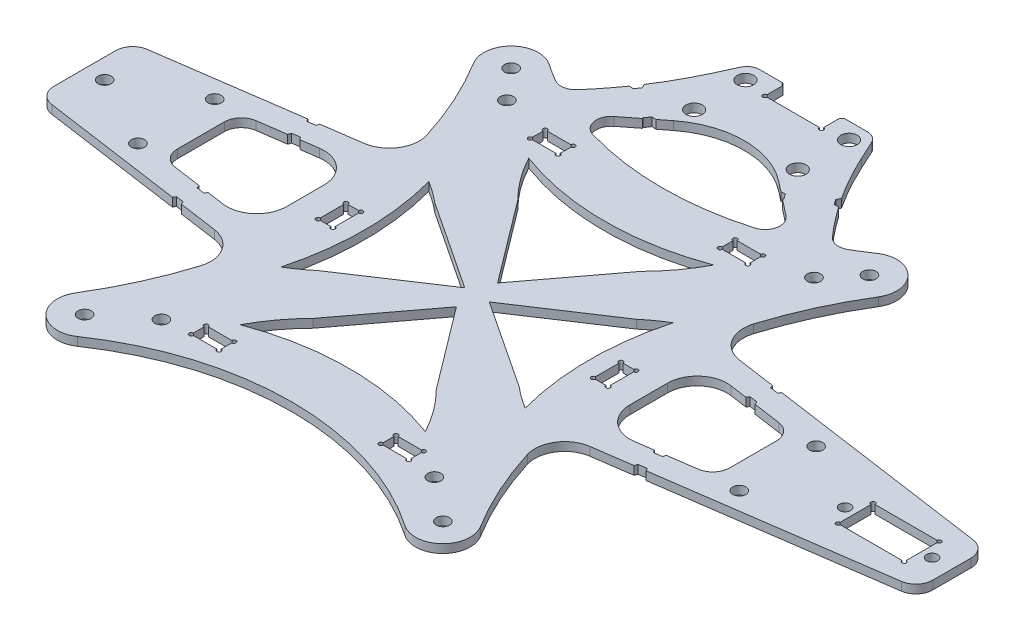
SolidWorks part; units mm, degrees
other "细节项目1" parameters "D5"=3.1, "D18"=3.2, "D24"=1.84, "D6"=8.6708, "D11"=4.977, "D15"=5.1762, "D16"=1.6515, "D17"=3.1, "D21"=13.484, "D14"=3.1, "D32"=6.4038, "D1"=40.7355, "D2"=35.8432, "D3"=28, "D4"=40.1699, "D7"=36.5, "D8"=41.25, "D9"=46.5, "D10"=20, "D12"=32.5, "D13"=87.0157, "D19"=3.5, "D20"=2.5, "D22"=0.15, "D23"=0.525, "D25"=70.5, "D26"=9, "D27"=9, "D28"=9.5, "D29"=135, "D30"=15.9142, "D31"=16.8571, "D33"=75.3972
material "PPS"
ref_plane "前视基准面" through (0, 0, 0) normal (0, 0, 1) x (1, 0, 0)
ref_plane "上视基准面" through (0, 0, 0) normal (0, 1, 0) x (1, 0, 0)
ref_plane "右视基准面" through (0, 0, 0) normal (1, 0, 0) x (0, 0, -1)
sketch "草图1" plane through (0, 0, 0) normal (0, 1, 0) x (1, 0, 0)
  line L3 (-133.7177, 0) -> (146.3754, 0) construction
  line L56 (0, 96.0639) -> (0, -115.1457) construction
  line L65 (-25.5, 41.5) -> (-19, 41.5)
  line L66 (-34, 3.25) -> (-30.5, 3.25)
  line L70 (-34, 3.25) -> (-34, -3.25)
  line L76 (-34, -3.25) -> (-30.5, -3.25)
  line L80 (-30.5, 3.25) -> (-30.5, -3.25)
  line L81 (-25.5, -38) -> (-19, -38)
  line L82 (-25.5, -38) -> (-25.5, -41.5)
  line L83 (-25.5, -41.5) -> (-19, -41.5)
  line L84 (-19, -38) -> (-19, -41.5)
  line L85 (-19, 38) -> (-19, 41.5)
  line L86 (-25.5, 38) -> (-19, 38)
  line L142 (-25.5, 38) -> (-25.5, 41.5)
  line L143 (25.5, 38) -> (25.5, 41.5)
  line L144 (25.5, 38) -> (19, 38)
  line L145 (19, 38) -> (19, 41.5)
  line L146 (19, -38) -> (19, -41.5)
  line L147 (25.5, -41.5) -> (19, -41.5)
  line L148 (25.5, -38) -> (25.5, -41.5)
  line L149 (25.5, -38) -> (19, -38)
  line L150 (30.5, 3.25) -> (30.5, -3.25)
  line L151 (34, -3.25) -> (30.5, -3.25)
  line L152 (34, 3.25) -> (34, -3.25)
  line L153 (34, 3.25) -> (30.5, 3.25)
  line L154 (25.5, 41.5) -> (19, 41.5)
  line L155 (77.65, -2.1518) -> (77.65, -4) construction
  line L156 (74.85, 4) -> (77.65, 4) construction
  line L157 (74.85, 4) -> (74.85, 2.1768) construction
  line L158 (74.85, -4) -> (77.65, -4) construction
  line L159 (77.65, 4) -> (77.65, 2.1518) construction
  line L160 (74.85, -2.1768) -> (74.85, -4) construction
  line L161 (96.5, 7.6653) -> (96.5, -9.1503) construction
  line L162 (88.75, 4.1) -> (104.25, 4.1)
  line L163 (88.75, 4.1) -> (88.75, -4.1)
  line L164 (88.75, -4.1) -> (104.25, -4.1)
  line L165 (104.25, 4.1) -> (104.25, -4.1)
  line L166 (-96.5, 7.6653) -> (-96.5, -9.1503) construction
  line L171 (-74.85, -2.1768) -> (-74.85, -4) construction
  line L172 (-77.65, 4) -> (-77.65, 2.1518) construction
  line L173 (-74.85, -4) -> (-77.65, -4) construction
  line L174 (-74.85, 4) -> (-74.85, 2.1768) construction
  line L175 (-74.85, 4) -> (-77.65, 4) construction
  line L176 (-77.65, -2.1518) -> (-77.65, -4) construction
  line L177 (111.35, 7.9303) -> (111.35, -7.9303)
  line L178 (111.35, 7.9303) -> (36.25, 18.6361)
  line L179 (111.35, -7.9303) -> (36.25, -18.6361)
  line L184 (14.4296, 23.978) -> (0, 4.8247)
  line L186 (-14.4296, 23.978) -> (0, 4.8247)
  line L187 (23.6257, -13.733) -> (2.8757, 0)
  line L188 (23.6257, 13.733) -> (2.8757, 0)
  line L191 (-91.953, 10.6955) -> (-91.953, -10.6955)
  line L192 (-36.25, 18.6361) -> (-91.953, 10.6955)
  line L193 (-91.953, -10.6955) -> (-36.25, -18.6361)
  line L195 (-64.75, -8.9672) -> (-64.75, 8.9672)
  line L196 (-64.75, 8.9672) -> (-40.25, 12.4598)
  line L197 (-40.25, 12.4598) -> (-40.25, -12.4598)
  line L198 (-64.75, -8.9672) -> (-40.25, -12.4598)
  line L199 (64.75, 8.9672) -> (40.25, 12.4598)
  line L200 (40.25, 12.4598) -> (40.25, -12.4598)
  line L201 (64.75, -8.9672) -> (40.25, -12.4598)
  line L202 (64.75, 8.9672) -> (64.75, -8.9672)
  line L211 (-23.6257, 13.733) -> (-2.8757, 0)
  line L212 (-23.6257, -13.733) -> (-2.8757, 0)
  line L213 (-14.4296, -23.978) -> (0, -4.8247)
  line L214 (14.4296, -23.978) -> (0, -4.8247)
  circle A0 centre (-36, 43) radius 1.55
  circle A1 centre (-32, -42) radius 1.55
  circle A2 centre (32, -42) radius 1.55
  circle A3 centre (36, 43) radius 1.55
  circle A4 centre (42, 50) radius 1.55
  circle A5 centre (42, -50) radius 1.55
  circle A6 centre (-42, -50) radius 1.55
  circle A7 centre (-42, 50) radius 1.55
  arc A8 (74.85, 2.1768) -> (74.85, -2.1768) centre (76.2307, 0) ccw construction
  arc A9 (77.65, -2.1518) -> (77.65, 2.1518) centre (76.2307, 0) ccw construction
  circle A10 centre (106.7, 0) radius 1.3
  circle A11 centre (86.3, 0) radius 1.3
  arc A14 (-77.65, -2.1518) -> (-77.65, 2.1518) centre (-76.2307, 0) cw construction
  arc A15 (-74.85, 2.1768) -> (-74.85, -2.1768) centre (-76.2307, 0) cw construction
  arc A18 (-38.3898, 55.2892) -> (38.3898, 55.2892) centre (0, 111.5317) ccw
  arc A20 (47.4575, 46.6496) -> (36.25, 18.6361) centre (123.4458, 0) ccw
  arc A21 (47.4575, 46.6496) -> (38.3898, 55.2892) centre (42, 50) ccw
  arc A22 (-38.3898, -55.2892) -> (38.3898, -55.2892) centre (0, -111.5317) cw
  arc A23 (47.4575, -46.6496) -> (36.25, -18.6361) centre (123.4458, 0) cw
  arc A24 (47.4575, -46.6496) -> (38.3898, -55.2892) centre (42, -50) cw
  arc A26 (-47.4575, -46.6496) -> (-38.3898, -55.2892) centre (-42, -50) ccw
  arc A27 (-47.4575, -46.6496) -> (-36.25, -18.6361) centre (-123.4458, 0) ccw
  arc A28 (-47.4575, 46.6496) -> (-38.3898, 55.2892) centre (-42, 50) cw
  arc A30 (-47.4575, 46.6496) -> (-36.25, 18.6361) centre (-123.4458, 0) cw
  arc A34 (-14.4296, 23.978) -> (-21.6836, 33.816) centre (14.4807, 52.8883) cw
  arc A35 (-21.6836, 33.816) -> (21.6836, 33.816) centre (0, 91.9966) ccw
  arc A36 (14.4296, 23.978) -> (21.6836, 33.816) centre (-14.4807, 52.8883) ccw
  arc A37 (23.6257, 13.733) -> (28.6529, 17.3535) centre (49.9637, -17.5386) cw
  arc A38 (28.6529, 17.3535) -> (28.6529, -17.3535) centre (92.8745, 0) ccw
  arc A39 (23.6257, -13.733) -> (28.6529, -17.3535) centre (49.436, 16.806) ccw
  circle A43 centre (70.5, 9) radius 1.55
  circle A44 centre (70.5, -9) radius 1.55
  circle A45 centre (-70.5, -9) radius 1.55
  circle A46 centre (-70.5, 9) radius 1.55
  circle A47 centre (-87.3, 0) radius 1.55
  arc A48 (-23.6257, -13.733) -> (-28.6529, -17.3535) centre (-49.436, 16.806) cw
  arc A49 (-28.6529, 17.3535) -> (-28.6529, -17.3535) centre (-92.8745, 0) cw
  arc A50 (-23.6257, 13.733) -> (-28.6529, 17.3535) centre (-49.9637, -17.5386) ccw
  arc A51 (14.4296, -23.978) -> (21.6836, -33.816) centre (-14.4807, -52.8883) cw
  arc A52 (-21.6836, -33.816) -> (21.6836, -33.816) centre (0, -91.9966) cw
  arc A53 (-14.4296, -23.978) -> (-21.6836, -33.816) centre (14.4807, -52.8883) ccw
  point P71 (0, 0)
  point P81 (-34, 0)
  point P118 (0, 0)
  point P140 (-40.25, 0)
  point P148 (0, 0)
  point P149 (-64.75, 0)
  point P150 (0, 0)
  point P151 (34, 18.9559)
  point P152 (37.6986, 18.4296)
extrude "凸台-拉伸1" add sketch "草图1" along normal blind 2
fillet "圆角1" radius 4 8 edges at (111.35, 1, -7.9303) (111.35, 1, 7.9303) (-91.953, 1, 10.6955) (-91.953, 1, -10.6955) (-64.75, 1, 8.9672) (-64.75, 1, -8.9672) (64.75, 1, 8.9672) (64.75, 1, -8.9672)
fillet "圆角2" radius 7 8 edges at (36.25, 1, -18.6361) (36.25, 1, 18.6361) (-36.25, 1, 18.6361) (-36.25, 1, -18.6361) (40.25, 1, 12.4598) (40.25, 1, -12.4598) (-40.25, 1, 12.4598) (-40.25, 1, -12.4598)
sketch "光流接口-修改" plane through (0, 0, 0) normal (0, 1, 0) x (1, 0, 0)
  line L0 (30.4025, 52.8577) -> (32.0373, 51.0287)
  line L1 (-32.0373, 51.0287) -> (-30.4025, 52.8577)
  line L2 (-6.65, 78.8853) -> (-6.65, 74.1353)
  line L3 (-6.65, 74.1353) -> (-0.15, 74.1353)
  line L4 (-0.15, 74.1353) -> (-0.15, 78.8853) construction
  line L5 (-12.6234, 78.8853) -> (-6.65, 78.8853)
  line L6 (-0.15, 74.1353) -> (0.15, 74.1353)
  line L7 (6.65, 74.1353) -> (0.15, 74.1353)
  line L8 (0.15, 74.1353) -> (0.15, 78.8853) construction
  line L9 (6.65, 78.8853) -> (6.65, 74.1353)
  line L10 (12.6234, 78.8853) -> (6.65, 78.8853)
  line L12 (12.3359, 58.409) -> (29.4648, 44.9866)
  line L13 (15.3497, 77.1372) -> (17.348, 72.7857)
  line L14 (0, -39.4607) -> (0, 39.4607) construction
  line L15 (-15.3497, 77.1372) -> (-17.348, 72.7857)
  line L16 (-12.3359, 58.409) -> (-29.4648, 44.9866)
  line L17 (-12.6234, 78.8853) -> (12.6234, 78.8853) construction
  circle A38 centre (-12.15, 75.08) radius 1.925
  circle A39 centre (-12.15, 63.05) radius 1.925
  circle A40 centre (12.15, 63.05) radius 1.925
  circle A41 centre (12.15, 75.08) radius 1.925
  circle A42 centre (-36, 43) radius 1.55
  circle A43 centre (36, 43) radius 1.55
  arc A44 (-37.8248, 46.5595) -> (-32.3705, 41.3187) centre (-36, 43) ccw
  arc A45 (37.8248, 46.5595) -> (32.3705, 41.3187) centre (36, 43) cw
  arc A46 (32.3705, 41.3187) -> (29.4648, 44.9866) centre (23.2968, 37.1154) ccw
  arc A47 (37.8248, 46.5595) -> (32.0373, 51.0287) centre (46.9489, 64.357) cw
  arc A48 (-12.3359, 58.409) -> (12.3359, 58.409) centre (0, 42.6665) cw
  arc A49 (17.348, 72.7857) -> (30.4025, 52.8577) centre (90.0489, 106.1709) ccw
  arc A50 (12.6234, 78.8853) -> (15.3497, 77.1372) centre (12.6234, 75.8853) cw
  arc A51 (-12.6234, 78.8853) -> (-15.3497, 77.1372) centre (-12.6234, 75.8853) ccw
  arc A52 (-17.348, 72.7857) -> (-30.4025, 52.8577) centre (-90.0489, 106.1709) cw
  arc A53 (-37.8248, 46.5595) -> (-32.0373, 51.0287) centre (-46.9489, 64.357) ccw
  arc A54 (-32.3705, 41.3187) -> (-29.4648, 44.9866) centre (-23.2968, 37.1154) cw
  arc A55 (-37.8248, 46.5595) -> (-32.3705, 41.3187) centre (-36, 43) ccw
  circle A56 centre (-36, 43) radius 1.55
  point P10 (0, 78.8853)
  dimension "D4" = 3.85
  dimension "D1" = 12.03
  dimension "D2" = 24.3
  dimension "D3" = 63.05
  dimension "D5" = 5.5
  dimension "D6" = 6.5
  dimension "D7" = 4.75
extrude "凸台-拉伸2" add sketch "光流接口-修改" along normal up to surface (2 mm away) from surface at 0 contours A48 L14 L17 A51 L15 A52 L1 A53 A44 A54 L16 A42 A39 A38 | L14 A48 L12 A46 A45 A47 L0 A49 L13 A50 L17 A40 A41 A43
sketch "线槽-草图" plane through (0, 0, 0) normal (0, 1, 0) x (1, 0, 0)
  line L1 (107.9145, 8.4201) -> (44.0177, 17.5288) construction
  line L5 (57.8515, 15.5567) -> (57.0683, 10.0623) construction
  line L6 (53.6304, 11.2089) -> (53.5387, 10.5654) construction
  line L7 (57.4599, 12.8095) -> (49.4026, 13.9581) construction
  line L8 (54.5679, 11.0753) -> (52.693, 11.3426)
  line L9 (54.7762, 10.389) -> (54.5679, 11.0753)
  line L10 (52.3012, 10.7418) -> (54.7762, 10.389)
  line L11 (52.693, 11.3426) -> (52.3012, 10.7418)
  line L12 (0, 0) -> (132.6638, 0) construction
  line L21 (0, -0.7474) -> (0, 57.4396) construction
  line L38 (61.3145, 9.457) -> (48.2379, 11.3211) construction
  line L39 (54.2302, 15.4164) -> (54.322, 16.0599) construction
  line L40 (53.2928, 15.55) -> (53.0845, 16.2363)
  line L41 (53.0845, 16.2363) -> (55.5595, 15.8835)
  line L42 (55.5595, 15.8835) -> (55.1677, 15.2828)
  line L43 (55.1677, 15.2828) -> (53.2928, 15.55)
  line L44 (-54.2302, 15.4164) -> (-54.322, 16.0599) construction
  line L45 (-57.4599, 12.8095) -> (-49.4026, 13.9581) construction
  line L46 (-53.6304, 11.2089) -> (-53.5387, 10.5654) construction
  line L47 (-57.8515, 15.5567) -> (-57.0683, 10.0623) construction
  line L48 (-55.1677, 15.2828) -> (-53.2928, 15.55)
  line L49 (-55.5595, 15.8835) -> (-55.1677, 15.2828)
  line L50 (-53.0845, 16.2363) -> (-55.5595, 15.8835)
  line L51 (-53.2928, 15.55) -> (-53.0845, 16.2363)
  line L52 (-52.693, 11.3426) -> (-52.3012, 10.7418)
  line L53 (-52.3012, 10.7418) -> (-54.7762, 10.389)
  line L54 (-54.7762, 10.389) -> (-54.5679, 11.0753)
  line L55 (-54.5679, 11.0753) -> (-52.693, 11.3426)
  line L56 (-57.8515, -15.5567) -> (-57.0683, -10.0623) construction
  line L57 (-53.6304, -11.2089) -> (-53.5387, -10.5654) construction
  line L58 (-57.4599, -12.8095) -> (-49.4026, -13.9581) construction
  line L59 (-54.2302, -15.4164) -> (-54.322, -16.0599) construction
  line L60 (-54.5679, -11.0753) -> (-52.693, -11.3426)
  line L61 (-54.7762, -10.389) -> (-54.5679, -11.0753)
  line L62 (-52.3012, -10.7418) -> (-54.7762, -10.389)
  line L63 (-52.693, -11.3426) -> (-52.3012, -10.7418)
  line L64 (-53.2928, -15.55) -> (-53.0845, -16.2363)
  line L65 (-53.0845, -16.2363) -> (-55.5595, -15.8835)
  line L66 (-55.5595, -15.8835) -> (-55.1677, -15.2828)
  line L67 (-55.1677, -15.2828) -> (-53.2928, -15.55)
  line L68 (54.2302, -15.4164) -> (54.322, -16.0599) construction
  line L69 (57.4599, -12.8095) -> (49.4026, -13.9581) construction
  line L70 (53.6304, -11.2089) -> (53.5387, -10.5654) construction
  line L71 (57.8515, -15.5567) -> (57.0683, -10.0623) construction
  line L72 (55.1677, -15.2828) -> (53.2928, -15.55)
  line L73 (55.5595, -15.8835) -> (55.1677, -15.2828)
  line L74 (53.0845, -16.2363) -> (55.5595, -15.8835)
  line L75 (53.2928, -15.55) -> (53.0845, -16.2363)
  line L76 (52.693, -11.3426) -> (52.3012, -10.7418)
  line L77 (52.3012, -10.7418) -> (54.7762, -10.389)
  line L78 (54.7762, -10.389) -> (54.5679, -11.0753)
  line L79 (54.5679, -11.0753) -> (52.693, -11.3426)
  line L80 (23.8224, 61.2928) -> (90.0489, 106.1709) construction
  line L81 (23.1293, 62.333) -> (22.6942, 61.4327)
  line L82 (22.6942, 61.4327) -> (23.5317, 60.1928)
  line L83 (23.5317, 60.1928) -> (24.5317, 60.2635)
  line L84 (23.8224, 61.2928) -> (15.6892, 55.7813) construction
  line L85 (25.2489, 48.2902) -> (12.3359, 58.409) construction
  line L86 (16.0581, 54.522) -> (14.6563, 56.5907)
  line L87 (14.6563, 56.5907) -> (15.6563, 56.6628)
  line L88 (15.6563, 56.6628) -> (16.4957, 55.4241)
  line L89 (16.4957, 55.4241) -> (16.0581, 54.522)
  line L90 (-23.8224, 61.2928) -> (-15.6892, 55.7813) construction
  line L91 (-16.4957, 55.4241) -> (-16.0581, 54.522)
  line L92 (-15.6563, 56.6628) -> (-16.4957, 55.4241)
  line L93 (-14.6563, 56.5907) -> (-15.6563, 56.6628)
  line L94 (-16.0581, 54.522) -> (-14.6563, 56.5907)
  line L95 (-23.5317, 60.1928) -> (-24.5317, 60.2635)
  line L96 (-22.6942, 61.4327) -> (-23.5317, 60.1928)
  line L97 (-23.1293, 62.333) -> (-22.6942, 61.4327)
  arc A0 (23.1293, 62.333) -> (24.5317, 60.2635) centre (90.0489, 106.1709) ccw
  arc A1 (17.348, 72.7857) -> (30.4025, 52.8577) centre (90.0489, 106.1709) ccw construction
  arc A2 (-23.1293, 62.333) -> (-24.5317, 60.2635) centre (-90.0489, 106.1709) cw
  point P47 (54.7762, 10.389)
  point P49 (23.1293, 62.333)
  point P88 (16.076, 56.0434)
  dimension "D5" = 1
  dimension "D1" = 2.5
  dimension "D2" = 115
  dimension "D3" = 0.65
  dimension "D4" = 2.5
  dimension "D6" = 1
  dimension "D7" = 120
  dimension "D8" = 120
  dimension "D9" = 1
extrude "线槽" cut sketch "线槽-草图" along normal through all
sketch "草图10" plane through (0, 0, 0) normal (0, 1, 0) x (1, 0, 0)
  line L0 (0, 0) -> (0, -66.7571) construction
  line L1 (-6.65, 74.1353) -> (6.65, 74.1353) construction
  circle A0 centre (-77.65, 4) radius 0.5 construction
  circle A1 centre (-74.85, 4) radius 0.5 construction
  circle A2 centre (-77.65, -4) radius 0.5 construction
  circle A3 centre (-74.85, -4) radius 0.5 construction
  circle A4 centre (-25.5, 41.5) radius 0.5
  circle A5 centre (-19, 41.5) radius 0.5
  circle A6 centre (-25.5, 38) radius 0.5
  circle A7 centre (-19, 38) radius 0.5
  circle A8 centre (-34, 3.25) radius 0.5
  circle A9 centre (-30.5, 3.25) radius 0.5
  circle A10 centre (-34, -3.25) radius 0.5
  circle A11 centre (-30.5, -3.25) radius 0.5
  circle A12 centre (-25.5, -38) radius 0.5
  circle A13 centre (-19, -38) radius 0.5
  circle A14 centre (-25.5, -41.5) radius 0.5
  circle A15 centre (-19, -41.5) radius 0.5
  circle A16 centre (19, -41.5) radius 0.5
  circle A17 centre (25.5, -41.5) radius 0.5
  circle A18 centre (19, -38) radius 0.5
  circle A19 centre (25.5, -38) radius 0.5
  circle A20 centre (30.5, -3.25) radius 0.5
  circle A21 centre (34, -3.25) radius 0.5
  circle A22 centre (30.5, 3.25) radius 0.5
  circle A23 centre (34, 3.25) radius 0.5
  circle A24 centre (19, 38) radius 0.5
  circle A25 centre (25.5, 38) radius 0.5
  circle A26 centre (19, 41.5) radius 0.5
  circle A27 centre (25.5, 41.5) radius 0.5
  circle A28 centre (74.85, -4) radius 0.5 construction
  circle A29 centre (77.65, -4) radius 0.5 construction
  circle A30 centre (74.85, 4) radius 0.5 construction
  circle A31 centre (77.65, 4) radius 0.5 construction
  circle A32 centre (88.75, 4.1) radius 0.5
  circle A33 centre (104.25, 4.1) radius 0.5
  circle A34 centre (88.75, -4.1) radius 0.5
  circle A35 centre (104.25, -4.1) radius 0.5
  circle A37 centre (-6.65, 74.1353) radius 0.5
  circle A38 centre (6.65, 74.1353) radius 0.5
  circle A39 centre (-6.65, 78.8853) radius 0.5
  circle A40 centre (6.65, 78.8853) radius 0.5
  dimension "D1" = 1
extrude "直角刀口" cut sketch "草图10" along normal through all
fillet "圆角6" radius 3.5 4 edges at (31.7859, 1, -51.31) (25.2489, 1, -48.2902) (-31.7859, 1, -51.31) (-25.2489, 1, -48.2902)
sketch "底部维修槽-草图" plane through (0, 0, 0) normal (0, 1, 0) x (1, 0, 0)
  line L0 (0, 0) -> (151.2551, 0) construction
  line L1 (0, 0) -> (0, 91.1633) construction
  line L2 (15.25, 15.25) -> (10, 10) construction
  line L3 (16.1339, 14.3661) -> (10.8839, 9.1161)
  line L4 (14.3661, 16.1339) -> (9.1161, 10.8839)
  line L5 (10, 10) -> (0, 0) construction
  line L6 (-15.25, 15.25) -> (-10, 10) construction
  line L7 (-16.1339, 14.3661) -> (-10.8839, 9.1161)
  line L8 (-14.3661, 16.1339) -> (-9.1161, 10.8839)
  line L9 (15.25, -15.25) -> (10, -10) construction
  line L10 (16.1339, -14.3661) -> (10.8839, -9.1161)
  line L11 (14.3661, -16.1339) -> (9.1161, -10.8839)
  line L12 (-15.25, -15.25) -> (-10, -10) construction
  line L13 (-16.1339, -14.3661) -> (-10.8839, -9.1161)
  line L14 (-14.3661, -16.1339) -> (-9.1161, -10.8839)
  arc A3 (16.1339, 14.3661) -> (14.3661, 16.1339) centre (15.25, 15.25) ccw
  arc A4 (9.1161, 10.8839) -> (10.8839, 9.1161) centre (10, 10) ccw
  arc A5 (-16.1339, 14.3661) -> (-14.3661, 16.1339) centre (-15.25, 15.25) cw
  arc A6 (-9.1161, 10.8839) -> (-10.8839, 9.1161) centre (-10, 10) cw
  arc A7 (16.1339, -14.3661) -> (14.3661, -16.1339) centre (15.25, -15.25) cw
  arc A8 (9.1161, -10.8839) -> (10.8839, -9.1161) centre (10, -10) cw
  arc A9 (-16.1339, -14.3661) -> (-14.3661, -16.1339) centre (-15.25, -15.25) ccw
  arc A10 (-9.1161, -10.8839) -> (-10.8839, -9.1161) centre (-10, -10) ccw
  point P6 (12.625, 12.625)
  point P14 (-12.625, 12.625)
  point P21 (12.625, -12.625)
  point P28 (-12.625, -12.625)
  dimension "D4" = 1.25
  dimension "D1" = 20
  dimension "D2" = 45
  dimension "D3" = 30.5
extrude "切除-拉伸8" [suppressed] cut sketch "底部维修槽-草图" along normal blind 10
